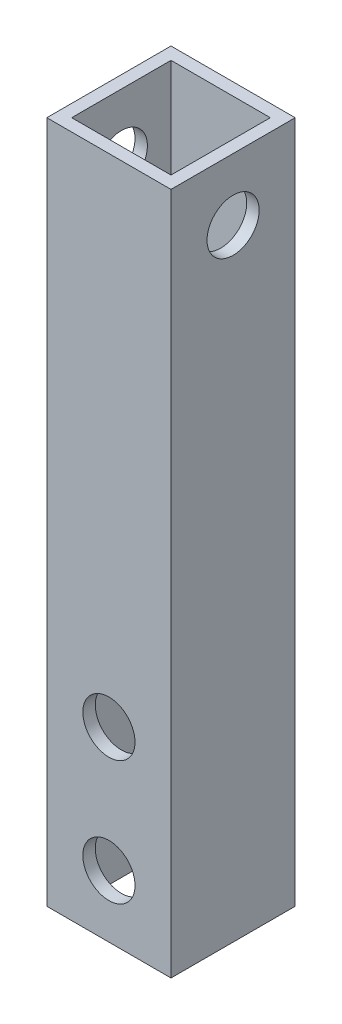
SolidWorks part; units mm, degrees
material "5052-H34"
ref_plane "正面" through (0, 0, 0) normal (0, 0, 1) x (1, 0, 0)
ref_plane "平面" through (0, 0, 0) normal (0, 1, 0) x (1, 0, 0)
ref_plane "右側面" through (0, 0, 0) normal (1, 0, 0) x (0, 0, -1)
sketch "ｽｹｯﾁ1" plane through (0, 0, 0) normal (0, 1, 0) x (1, 0, 0)
  line L1 (-5, 5) -> (5, 5)
  line L2 (-5, 5) -> (-5, -5)
  line L3 (-5, -5) -> (5, -5)
  line L4 (5, 5) -> (5, -5)
  line L5 (-5, 5) -> (5, -5) construction
  line L6 (-5, -5) -> (5, 5) construction
  point P0 (0, 0)
  dimension "D1" = 10
extrude "押し出し-薄板1" add sketch "ｽｹｯﾁ1" along normal blind 55 thin
sketch "ｽｹｯﾁ2" plane through (0, 0, 5) normal (0, 0, 1) x (1, 0, 0)
  line L0 (0, 0) -> (0, 15) construction
  line L1 (-5, 0) -> (5, 0) construction
  circle A0 centre (0, 15) radius 2.1
  circle A1 centre (0, 5) radius 2.1
  dimension "D1" = 4.2
  dimension "D2" = 5
  dimension "D3" = 10
extrude "ｶｯﾄ - 押し出し1" cut sketch "ｽｹｯﾁ2" against normal through all
sketch "ｽｹｯﾁ3" plane through (5, 0, 0) normal (1, 0, 0) x (0, 0, -1)
  line L0 (0, 55) -> (0, 40) construction
  line L1 (5, 55) -> (-5, 55) construction
  circle A0 centre (0, 40) radius 2.1 construction
  circle A1 centre (0, 50) radius 2.1
  dimension "D1" = 4.2
  dimension "D2" = 5
  dimension "D3" = 10
extrude "ｶｯﾄ - 押し出し2" cut sketch "ｽｹｯﾁ3" against normal through all
